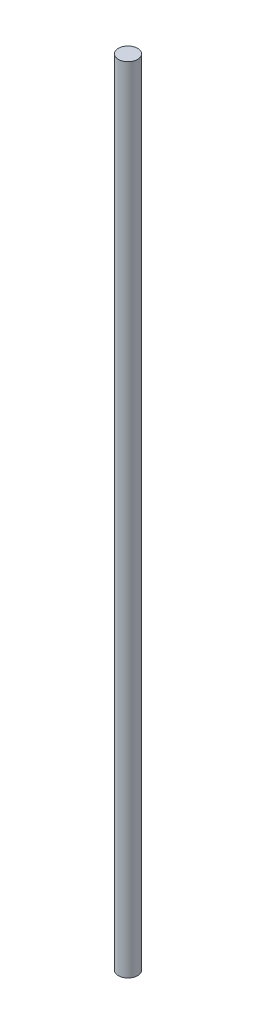
SolidWorks part; units mm, degrees
ref_plane "前视基准面" through (0, 0, 0) normal (0, 0, 1) x (1, 0, 0)
ref_plane "上视基准面" through (0, 0, 0) normal (0, 1, 0) x (1, 0, 0)
ref_plane "右视基准面" through (0, 0, 0) normal (1, 0, 0) x (0, 0, -1)
other "Configuration Table"
sketch "草图1" plane through (0, 0, 0) normal (0, 1, 0) x (1, 0, 0)
  circle A0 centre (0, 0) radius 2
extrude "凸台-拉伸1" add sketch "草图1" along normal blind 165
